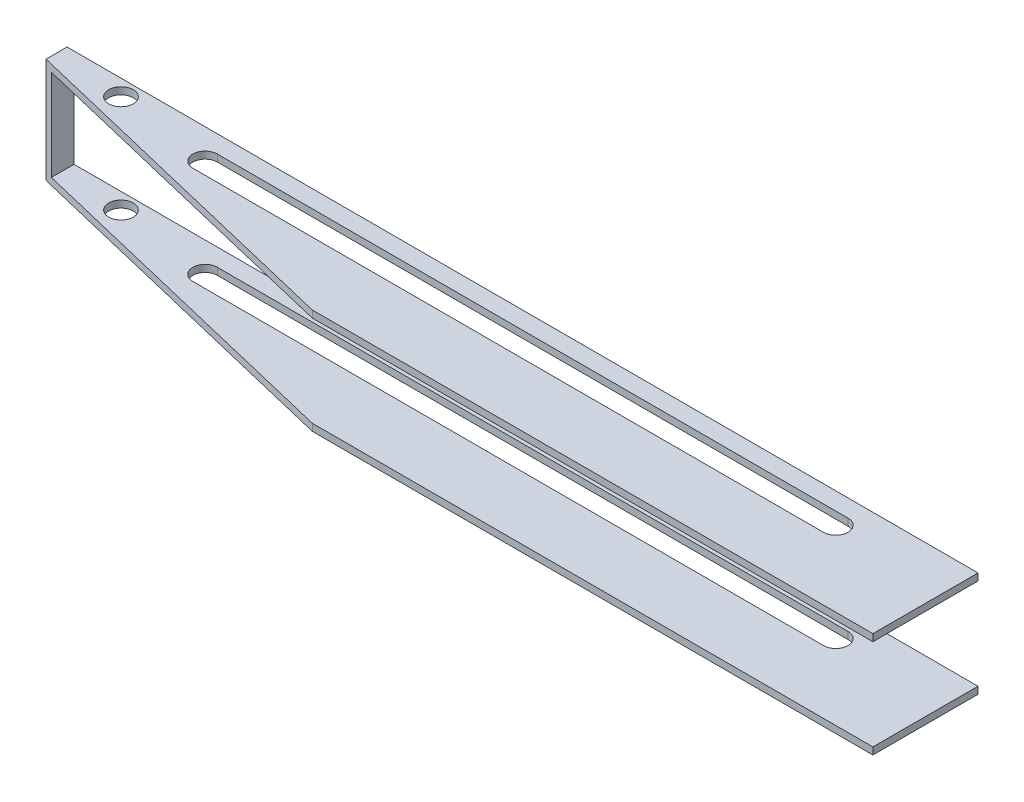
SolidWorks part; units mm, degrees
ref_plane "Front Plane" through (0, 0, 0) normal (0, 0, 1) x (1, 0, 0)
ref_plane "Top Plane" through (0, 0, 0) normal (0, 1, 0) x (1, 0, 0)
ref_plane "Right Plane" through (0, 0, 0) normal (1, 0, 0) x (0, 0, -1)
sketch "Sketch3" plane through (0, 0, 0) normal (0, 0, 1) x (1, 0, 0)
  line L0 (0, 0) -> (-29573.2583, 0) construction
  line L1 (-60.5374, -1.8599) -> (69.4626, -1.8599)
  line L2 (69.4626, -1.8599) -> (69.4626, -2.8599)
  line L3 (69.4626, -2.8599) -> (-59.5374, -2.8599)
  line L4 (-59.5374, -2.8599) -> (-59.5374, -15.8599)
  line L5 (-59.5374, -15.8599) -> (69.4626, -15.8599)
  line L6 (69.4626, -15.8599) -> (69.4626, -16.8599)
  line L7 (69.4626, -16.8599) -> (-60.5374, -16.8599)
  line L8 (-60.5374, -16.8599) -> (-60.5374, -1.8599)
  dimension "D1" = 130
  dimension "D2" = 1
  dimension "D3" = 1
  dimension "D4" = 15
extrude "Boss-Extrude1" add sketch "Sketch3" against normal blind 15
sketch "Sketch6" plane through (0, -1.8599, 0) normal (0, 1, 0) x (1, 0, 0)
  line L0 (-60.5374, 12) -> (-10.5374, 0)
  line L1 (-10.5374, 0) -> (-10.5374, -10.0649)
  line L2 (-10.5374, -10.0649) -> (-60.5374, -10.0649)
  line L3 (-60.5374, -10.0649) -> (-60.5374, 12)
  line L4 (69.4626, 15) -> (69.4626, 0) construction
  line L5 (69.4626, 0) -> (-60.5374, 0) construction
  line L7 (-60.5374, 15) -> (-60.5374, 0) construction
  dimension "D1" = 80
  dimension "D2" = 0
  dimension "D3" = 0
  dimension "D4" = 3
extrude "Cut-Extrude1" cut sketch "Sketch6" against normal through all
sketch "Sketch8" plane through (0, -1.8599, 0) normal (0, 1, 0) x (1, 0, 0)
  line L0 (-60.5374, 15) -> (-60.5374, 12) construction
  line L1 (69.4626, 15) -> (-60.5374, 15) construction
  circle A0 centre (-50.5374, 12.7) radius 1.75
  dimension "D1" = 3.5
  dimension "D2" = 10
  dimension "D3" = 2.3
extrude "Cut-Extrude2" cut sketch "Sketch8" against normal through all
sketch "Sketch12" plane through (0, -16.8599, 0) normal (0, -1, 0) x (1, 0, 0)
  line L0 (53.4154, -10.75) -> (-36.5846, -10.75) construction
  line L1 (53.4154, -12.5) -> (-36.5846, -12.5)
  line L2 (53.4154, -9) -> (-36.5846, -9)
  line L3 (-60.5374, -15) -> (69.4626, -15) construction
  arc A0 (53.4154, -12.5) -> (53.4154, -9) centre (53.4154, -10.75) ccw
  arc A1 (-36.5846, -9) -> (-36.5846, -12.5) centre (-36.5846, -10.75) ccw
  point P2 (8.4154, -10.75)
  dimension "D1" = 2.5
  dimension "D2" = 3.5
  dimension "D3" = 90
extrude "Cut-Extrude4" cut sketch "Sketch12" against normal through all
